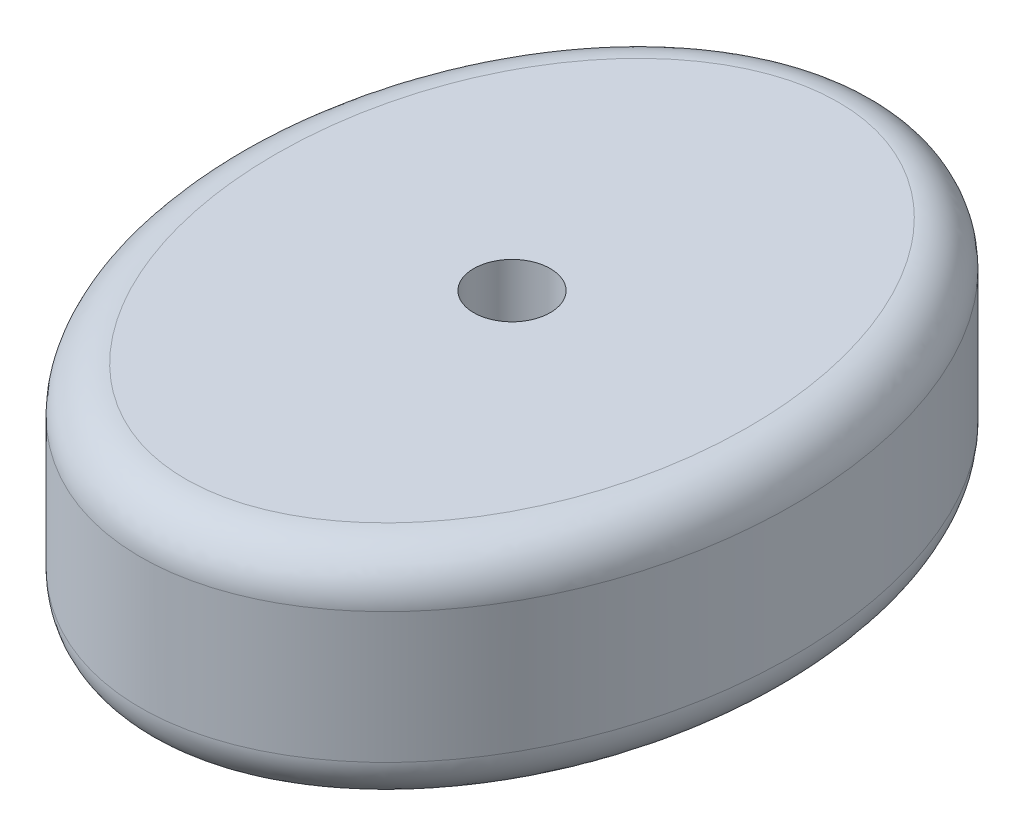
SolidWorks part; units mm, degrees
ref_plane "Front Plane" through (0, 0, 0) normal (0, 0, 1) x (1, 0, 0)
ref_plane "Top Plane" through (0, 0, 0) normal (0, 1, 0) x (1, 0, 0)
ref_plane "Right Plane" through (0, 0, 0) normal (1, 0, 0) x (0, 0, -1)
sketch "Sketch1" plane through (0, 0, 0) normal (0, 1, 0) x (1, 0, 0)
  line L0 (-6.25, 0) -> (6.25, 0) construction
  circle A6 centre (0, 0) radius 1.975
  ellipse E0 centre (0, 0) end of major axis (0, 8.25) minor radius 6.25
  dimension "D1" = 3.95
  dimension "D3" = 16.5
  dimension "12" = 12.5
extrude "Boss-Extrude1" add sketch "Sketch1" along normal blind 2.4
sketch "Sketch2" plane through (0, 2.4, 0) normal (0, 1, 0) x (1, 0, 0)
  circle A0 centre (0, 0) radius 0.85
  ellipse E0 centre (0, 0) end of major axis (0, 8.25) minor radius 6.25
  ellipse E1 centre (0, 0) end of major axis (0, 8.25) minor radius 6.25 construction
  dimension "D1" = 1.7
extrude "Boss-Extrude2" add sketch "Sketch2" along normal blind 2.5
fillet "Fillet1" radius 1 2 edges at (0, 0, -8.25) (0, 4.9, -8.25)
